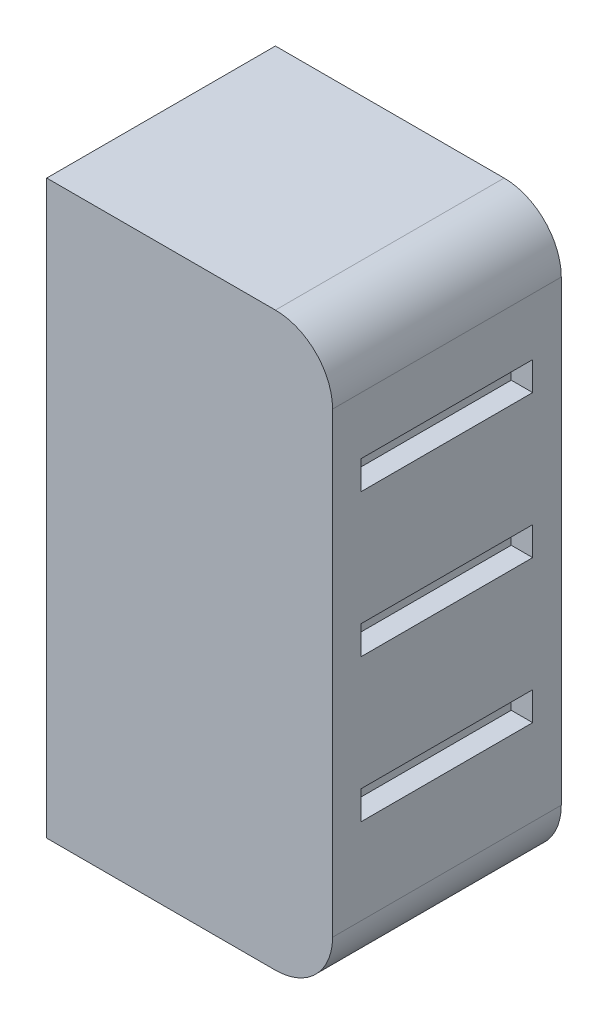
SolidWorks part; units mm, degrees
ref_plane "Front Plane" through (0, 0, 0) normal (0, 0, 1) x (1, 0, 0)
ref_plane "Top Plane" through (0, 0, 0) normal (0, 1, 0) x (1, 0, 0)
ref_plane "Right Plane" through (0, 0, 0) normal (1, 0, 0) x (0, 0, -1)
sketch "Sketch1" plane through (0, 0, 0) normal (0, 0, 1) x (1, 0, 0)
  line L1 (5, -10) -> (-5, -10)
  line L2 (5, -10) -> (5, 10)
  line L3 (5, 10) -> (-5, 10)
  line L4 (-5, -10) -> (-5, 10)
  line L5 (5, -10) -> (-5, 10) construction
  line L6 (5, 10) -> (-5, -10) construction
  point P0 (0, 0)
extrude "Boss-Extrude1" add sketch "Sketch1" along normal blind 8
fillet "Fillet3" radius 2 2 edges at (5, -10, 4) (5, 10, 4)
sketch "Sketch2" plane through (5, 0, 0) normal (1, 0, 0) x (0, 0, -1)
  line L1 (-1, -4) -> (-7, -4)
  line L2 (-1, -4) -> (-1, -5)
  line L3 (-1, -5) -> (-7, -5)
  line L4 (-7, -4) -> (-7, -5)
  line L5 (-1, -4) -> (-7, -5) construction
  line L6 (-1, -5) -> (-7, -4) construction
  point P0 (-4, -4.5)
  dimension "D1" = 3
  dimension "D2" = 4
extrude "Cut-Extrude1" cut sketch "Sketch2" against normal blind 0.75
pattern_linear "LPattern1" count 3 spacing 5 along (0, 1, 0) of "Cut-Extrude1"
